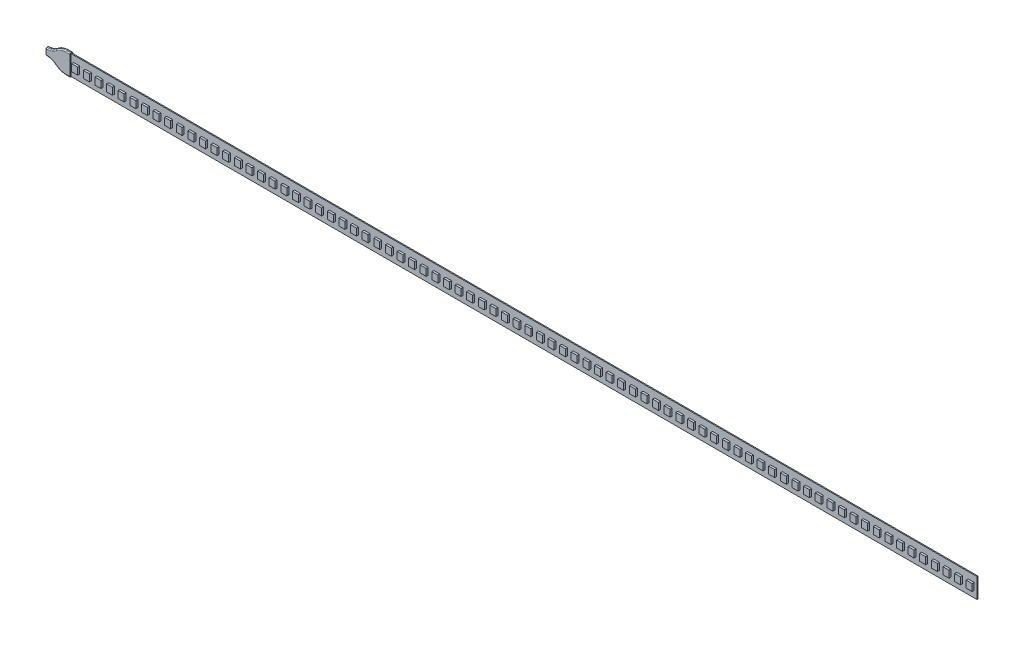
SolidWorks part; units mm, degrees
ref_plane "Frente" through (0, 0, 0) normal (0, 0, 1) x (1, 0, 0)
ref_plane "Topo" through (0, 0, 0) normal (0, 1, 0) x (1, 0, 0)
ref_plane "Lateral" through (0, 0, 0) normal (1, 0, 0) x (0, 0, -1)
sketch "Sketch1" plane through (0, 0, 0) normal (0, 0, 1) x (1, 0, 0)
  line L1 (17.5, -5) -> (-17.5, -5)
  line L2 (17.5, -5) -> (17.5, 5)
  line L3 (17.5, 5) -> (-17.5, 5)
  line L4 (-17.5, -5) -> (-17.5, 5)
  line L5 (17.5, -5) -> (-17.5, 5) construction
  line L6 (17.5, 5) -> (-17.5, -5) construction
  point P0 (0, 0)
  dimension "D1" = 35
  dimension "D2" = 10
extrude "Boss-Extrude1" add sketch "Sketch1" along normal blind 0.5
sketch "Sketch2" plane through (0, 0, 0.5) normal (0, 0, 1) x (1, 0, 0)
  line L0 (-17.5, 5) -> (-17.5, -5) construction
  line L1 (-16.0835, 1.75) -> (-13.0835, 1.75)
  line L2 (-16.0835, 1.75) -> (-16.0835, -1.75)
  line L3 (-16.0835, -1.75) -> (-13.0835, -1.75)
  line L4 (-13.0835, 1.75) -> (-13.0835, -1.75)
  line L5 (-13.0835, 0) -> (0, 0) construction
  dimension "D1" = 3.5
  dimension "D2" = 3
  dimension "D3" = 1.4165
extrude "Boss-Extrude2" add sketch "Sketch2" along normal blind 1
pattern_linear "LPattern1" count 6 spacing 5.833 along (1, 0, 0) of "Boss-Extrude2"
pattern_linear "LPattern2" count 13 spacing 35 along (1, 0, 0) of "Boss-Extrude1", "Boss-Extrude2", "LPattern1"
sketch "Sketch3" plane through (0, 0, 0) normal (0, 0, 1) x (1, 0, 0)
  line L0 (-17.5, 5.25) -> (-17.5, -5.25)
  line L1 (-17.5, -5.25) -> (-19.5, -5.25)
  line L2 (-29.5, -1.75) -> (-29.5, 1.75)
  line L3 (-17.5, 5.25) -> (-19.5, 5.25)
  line L4 (-17.5, 5) -> (-17.5, -5) construction
  line L5 (-29.5, 1.75) -> (-36.5804, 1.75) construction
  line L6 (-36.5804, 1.75) -> (-36.5804, -1.75) construction
  line L7 (-36.5804, -1.75) -> (-29.5, -1.75) construction
  line L8 (-17.5, 0) -> (-29.5, 0) construction
  line L9 (-19.5, 5.25) -> (-19.5, -5.25) construction
  arc A0 (-19.5, -5.25) -> (-24.5, -3.5) centre (-19.5, 2.7679) cw
  arc A1 (-24.5, -3.5) -> (-29.5, -1.75) centre (-29.5, -9.7679) ccw
  arc A2 (-19.5, 5.25) -> (-24.5, 3.5) centre (-19.5, -2.7679) ccw
  arc A3 (-24.5, 3.5) -> (-29.5, 1.75) centre (-29.5, 9.7679) cw
  point P0 (-17.5, 0)
  dimension "D1" = 10.5
  dimension "D2" = 2
  dimension "D3" = 10
  dimension "D4" = 3.5
extrude "Boss-Extrude3" add sketch "Sketch3" along normal blind 1 and the other way blind 0.5
fillet "Fillet1" radius 0.5 12 edges at (-26.8513, 2.2001, -0.5) (-22.1487, 4.7999, -0.5) (-26.8513, 2.2001, 1) (-22.1487, 4.7999, 1) (-18.5, 5.25, -0.5) (-18.5, 5.25, 1) (-26.8513, -2.2001, -0.5) (-22.1487, -4.7999, -0.5) (-26.8513, -2.2001, 1) (-22.1487, -4.7999, 1) (-18.5, -5.25, -0.5) (-18.5, -5.25, 1)
